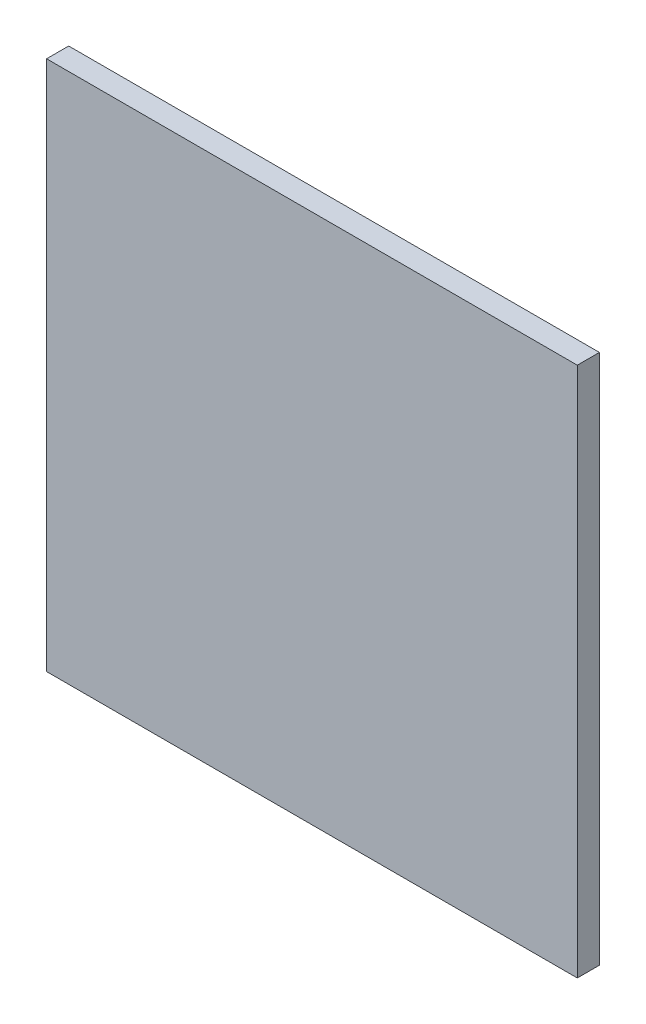
SolidWorks part; units mm, degrees
ref_plane "Front Plane" through (0, 0, 0) normal (0, 0, 1) x (1, 0, 0)
ref_plane "Top Plane" through (0, 0, 0) normal (0, 1, 0) x (1, 0, 0)
ref_plane "Right Plane" through (0, 0, 0) normal (1, 0, 0) x (0, 0, -1)
sketch "Sketch1" plane through (0, 0, 0) normal (0, 0, 1) x (1, 0, 0)
  line L1 (0, 0) -> (3048, 0)
  line L2 (0, 0) -> (0, 3048)
  line L3 (0, 3048) -> (3048, 3048)
  line L4 (3048, 0) -> (3048, 3048)
extrude "Boss-Extrude1" add sketch "Sketch1" along normal blind 127
